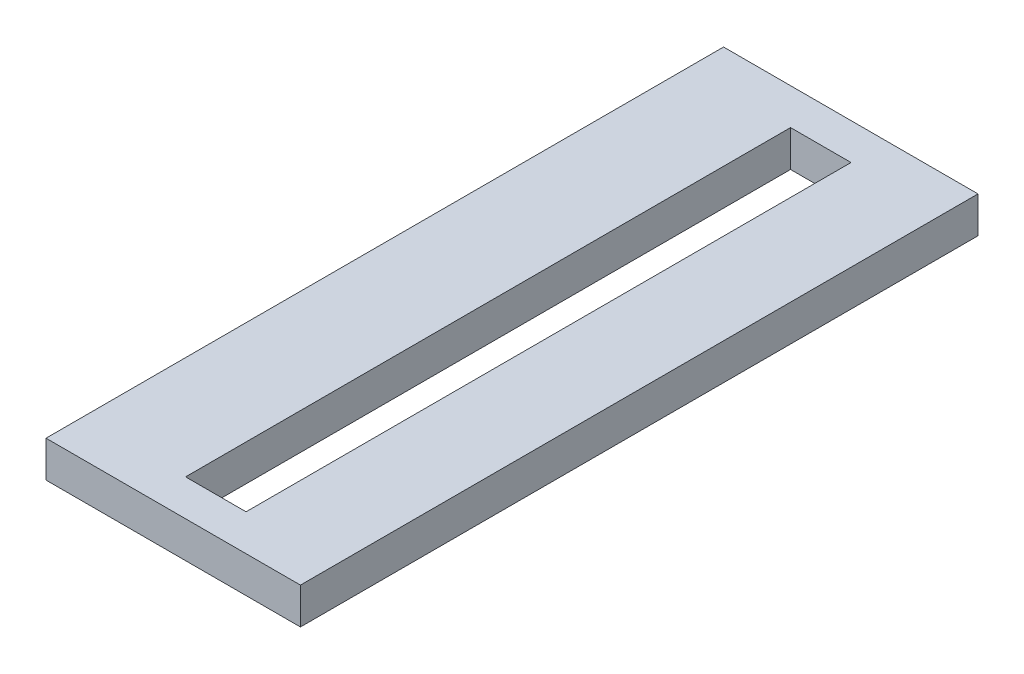
SolidWorks part; units mm, degrees
ref_plane "Plan de face" through (0, 0, 0) normal (0, 0, 1) x (1, 0, 0)
ref_plane "Plan de dessus" through (0, 0, 0) normal (0, 1, 0) x (1, 0, 0)
ref_plane "Plan de droite" through (0, 0, 0) normal (1, 0, 0) x (0, 0, -1)
sketch "Esquisse1" plane through (0, 0, 0) normal (0, 1, 0) x (1, 0, 0)
  line L0 (-44.3068, 0) -> (16.7085, 0) construction
  line L1 (44.3068, 28) -> (23.2777, 28)
  line L2 (44.3068, 28) -> (44.3068, -28)
  line L3 (44.3068, -28) -> (23.2777, -28)
  line L5 (44.3068, 28) -> (-44.3068, -28) construction
  line L6 (44.3068, -28) -> (-44.3068, 28) construction
  line L7 (23.2777, 28) -> (23.2777, -28)
  line L12 (-8.2876, 25) -> (-13.2876, -25) construction
  line L13 (-8.2876, -25) -> (-13.2876, 25) construction
  line L14 (31.8133, -25) -> (36.8133, -25)
  line L15 (31.8133, 25) -> (31.8133, -25)
  line L16 (31.8133, 25) -> (36.8133, 25)
  line L17 (36.8133, 25) -> (36.8133, -25)
  point P0 (0, 0)
  point P6 (-10.7876, 0)
  dimension "D2" = 56
  dimension "D3" = 5
  dimension "D4" = 50
extrude "BASE" add sketch "Esquisse1" along normal blind 3
